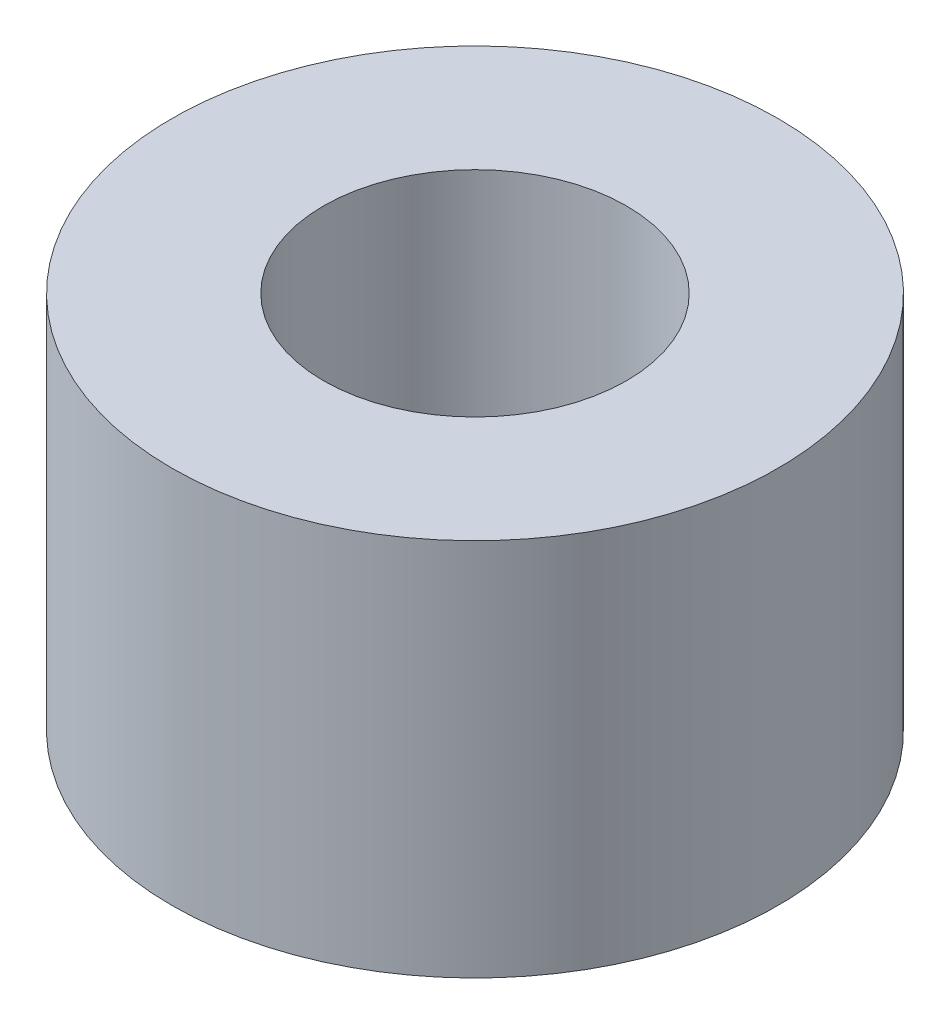
SolidWorks part; units mm, degrees
ref_plane "Front Plane" through (0, 0, 0) normal (0, 0, 1) x (1, 0, 0)
ref_plane "Top Plane" through (0, 0, 0) normal (0, 1, 0) x (1, 0, 0)
ref_plane "Right Plane" through (0, 0, 0) normal (1, 0, 0) x (0, 0, -1)
sketch "Sketch1" plane through (0, 0, 0) normal (0, 1, 0) x (1, 0, 0)
  circle A0 centre (5.5848, 0) radius 4
  circle A1 centre (5.5848, 0) radius 2
  dimension "D1" = 8
  dimension "D2" = 4
extrude "Boss-Extrude1" add sketch "Sketch1" along normal blind 5
